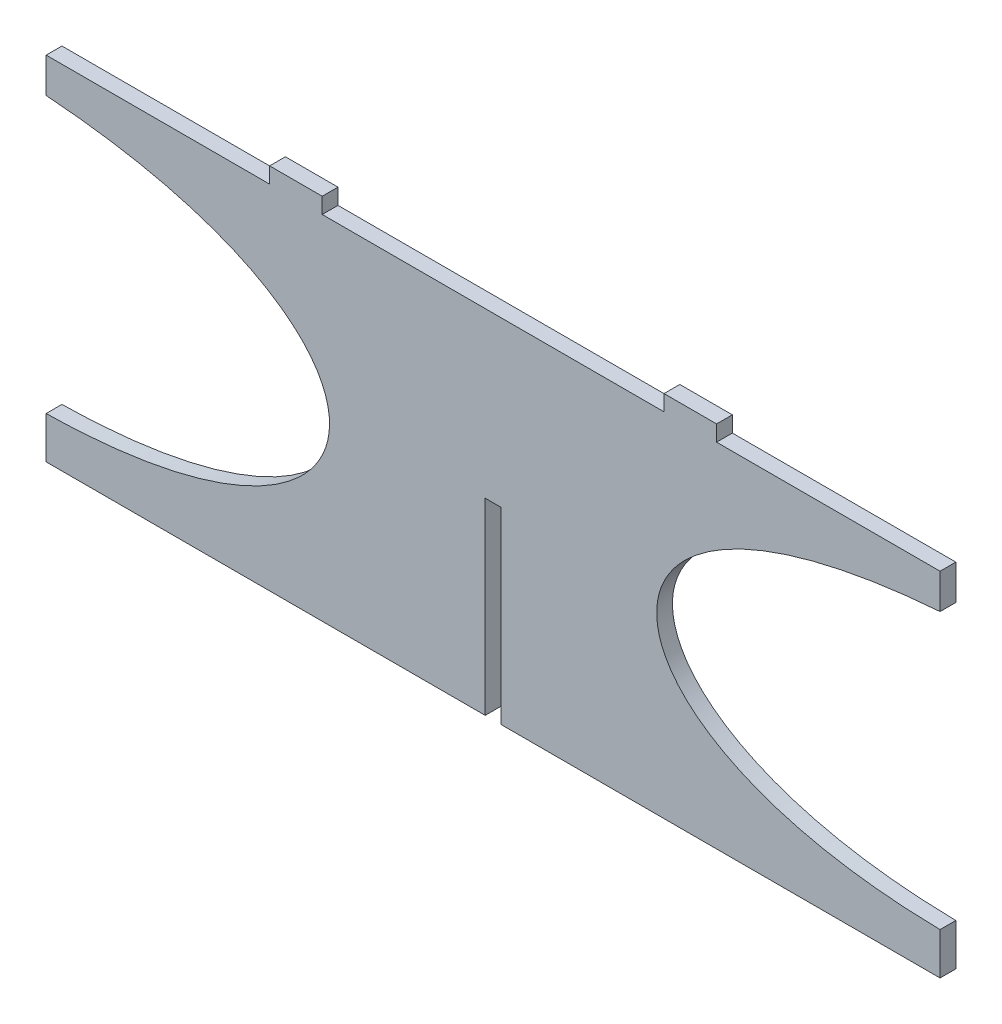
SolidWorks part; units mm, degrees
ref_plane "Plano frontal" through (0, 0, 0) normal (0, 0, 1) x (1, 0, 0)
ref_plane "Plano superior" through (0, 0, 0) normal (0, 1, 0) x (1, 0, 0)
ref_plane "Plano direito" through (0, 0, 0) normal (1, 0, 0) x (0, 0, -1)
sketch "Model" plane through (0, 0, 0) normal (0, 0, 1) x (1, 0, 0)
  line L19 (-58.8502, -89.6424) -> (-58.8502, -94.0776)
  line L20 (-58.8502, -128.9929) -> (-58.8502, -134.309)
  line L21 (-58.8502, -134.309) -> (-3.1835, -134.309)
  line L22 (-3.1835, -134.309) -> (-3.1835, -110.4605)
  line L23 (-3.1835, -110.4605) -> (-1.1835, -110.4605)
  line L24 (-1.1835, -110.4605) -> (-1.1835, -134.309)
  line L25 (-1.1835, -134.309) -> (54.4831, -134.309)
  line L26 (54.4831, -134.309) -> (54.4831, -128.9929)
  line L27 (54.4831, -94.0776) -> (54.4831, -89.6424)
  line L28 (54.4831, -89.6424) -> (26.1498, -89.6424)
  line L29 (26.1498, -89.6424) -> (26.1498, -87.6372)
  line L30 (26.1498, -87.6372) -> (19.4831, -87.6372)
  line L31 (19.4831, -87.6372) -> (19.4831, -89.6424)
  line L32 (19.4831, -89.6424) -> (-23.8502, -89.6424)
  line L33 (-23.8502, -89.6424) -> (-23.8502, -87.6372)
  line L34 (-23.8502, -87.6372) -> (-30.5169, -87.6372)
  line L35 (-30.5169, -87.6372) -> (-30.5169, -89.6424)
  line L36 (-30.5169, -89.6424) -> (-58.8502, -89.6424)
  spline S322 degree 3 poles (-58.8502, -94.0776) (-9.0376, -97.7844) (-12.8956, -128.2849) (-58.8502, -128.9929) knots 0.047619 0.047619 0.047619 0.047619 0.095238 0.095238 0.095238 0.095238
  spline S323 degree 3 poles (54.4831, -128.9929) (8.5266, -128.2849) (4.6696, -97.7845) (54.4831, -94.0776) knots 0.428571 0.428571 0.428571 0.428571 0.47619 0.47619 0.47619 0.47619
extrude "Ressalto-extrusão1" add sketch "Model" along normal blind 2
